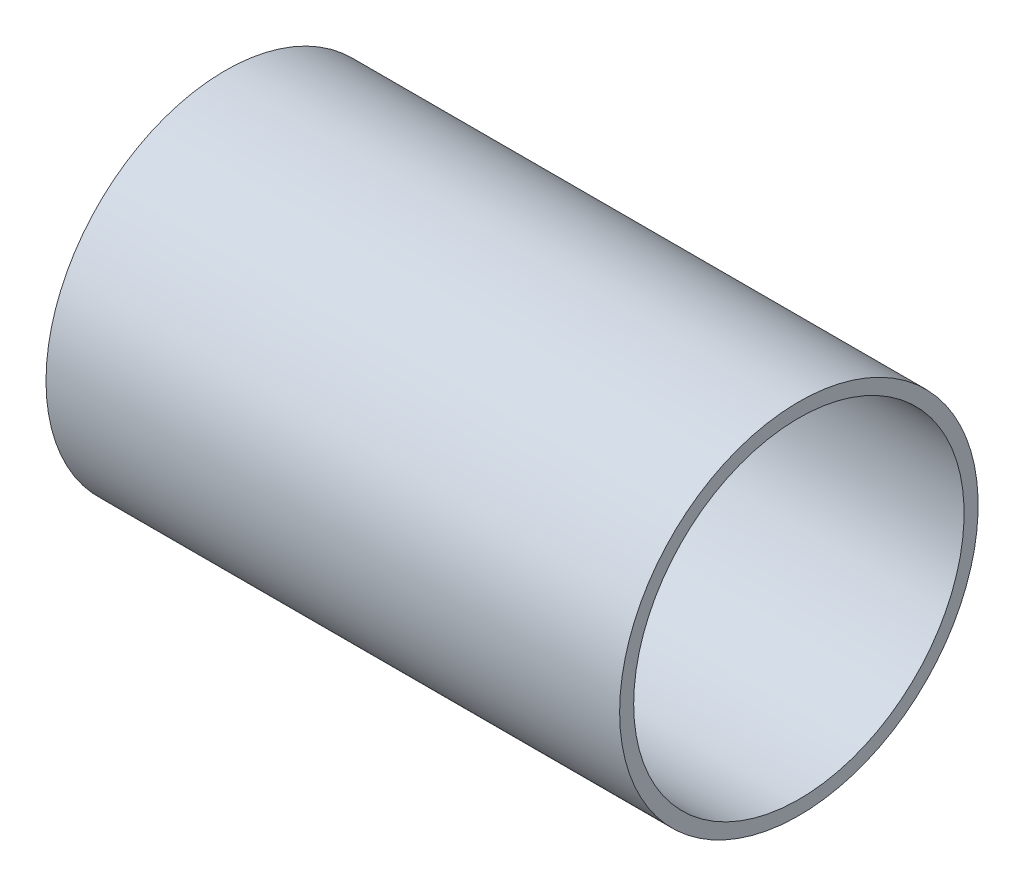
SolidWorks part; units mm, degrees
material "6061-T6 (SS)"
ref_plane "Front Plane" through (0, 0, 0) normal (0, 0, 1) x (1, 0, 0)
ref_plane "Top Plane" through (0, 0, 0) normal (0, 1, 0) x (1, 0, 0)
ref_plane "Right Plane" through (0, 0, 0) normal (1, 0, 0) x (0, 0, -1)
sketch "Sketch1" plane through (0, 0, 0) normal (0, 1, 0) x (1, 0, 0)
  line L0 (-72.894, 0) -> (78.2697, 0) construction
  line L1 (-25.4, 15.875) -> (-25.4, 14.6304)
  line L2 (-25.4, 15.875) -> (25.4, 15.875)
  line L3 (-25.4, 14.6304) -> (25.4, 14.6304)
  line L4 (25.4, 15.875) -> (25.4, 14.6304)
  line L5 (0, 0) -> (0, 14.6304) construction
  dimension "D1" = 31.75
  dimension "D2" = 1.2446
  dimension "D3" = 50.8
revolve "Revolve1" add sketch "Sketch1" angle 360 about L0
